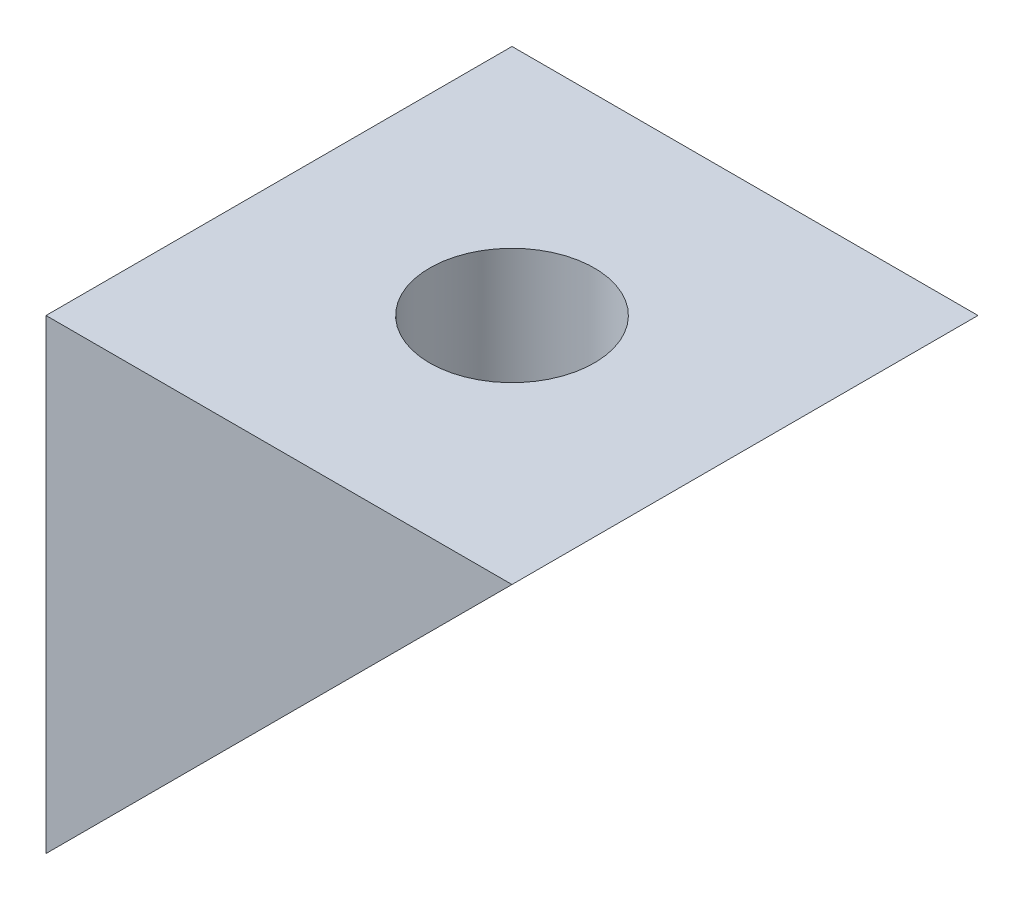
SolidWorks part; units mm, degrees
ref_plane "Plan de face" through (0, 0, 0) normal (0, 0, 1) x (1, 0, 0)
ref_plane "Plan de dessus" through (0, 0, 0) normal (0, 1, 0) x (1, 0, 0)
ref_plane "Plan de droite" through (0, 0, 0) normal (1, 0, 0) x (0, 0, -1)
sketch "Esquisse1" plane through (0, 0, 0) normal (0, 0, 1) x (1, 0, 0)
  line L0 (0, 0) -> (0, 12)
  line L1 (0, 12) -> (12, 12)
  line L2 (12, 12) -> (0, 0)
  dimension "D1" = 12
extrude "Boss.-Extru.1" add sketch "Esquisse1" along normal blind 12
sketch "Esquisse2" plane through (0, 12, 0) normal (0, 1, 0) x (1, 0, 0)
  line L0 (0, -6) -> (12, -6) construction
  line L1 (0, -12) -> (0, 0) construction
  line L2 (12, -12) -> (12, 0) construction
  line L3 (6, 0) -> (6, -12) construction
  line L4 (12, 0) -> (0, 0) construction
  line L5 (12, -12) -> (0, -12) construction
  circle A0 centre (6, -6) radius 2.12
extrude "Enlèv. mat.-Extru.1" cut sketch "Esquisse2" against normal blind 12
sketch "Esquisse3" plane through (0, 0, 0) normal (-1, 0, 0) x (0, 0, 1)
  line L0 (6, 12) -> (6, 0) construction
  line L1 (12, 12) -> (0, 12) construction
  line L2 (12, 0) -> (0, 0) construction
  line L3 (0, 6) -> (12, 6) construction
  line L4 (0, 12) -> (0, 0) construction
  line L5 (12, 12) -> (12, 0) construction
  circle A0 centre (6, 6) radius 2.12
extrude "Enlèv. mat.-Extru.2" cut sketch "Esquisse3" against normal blind 12
